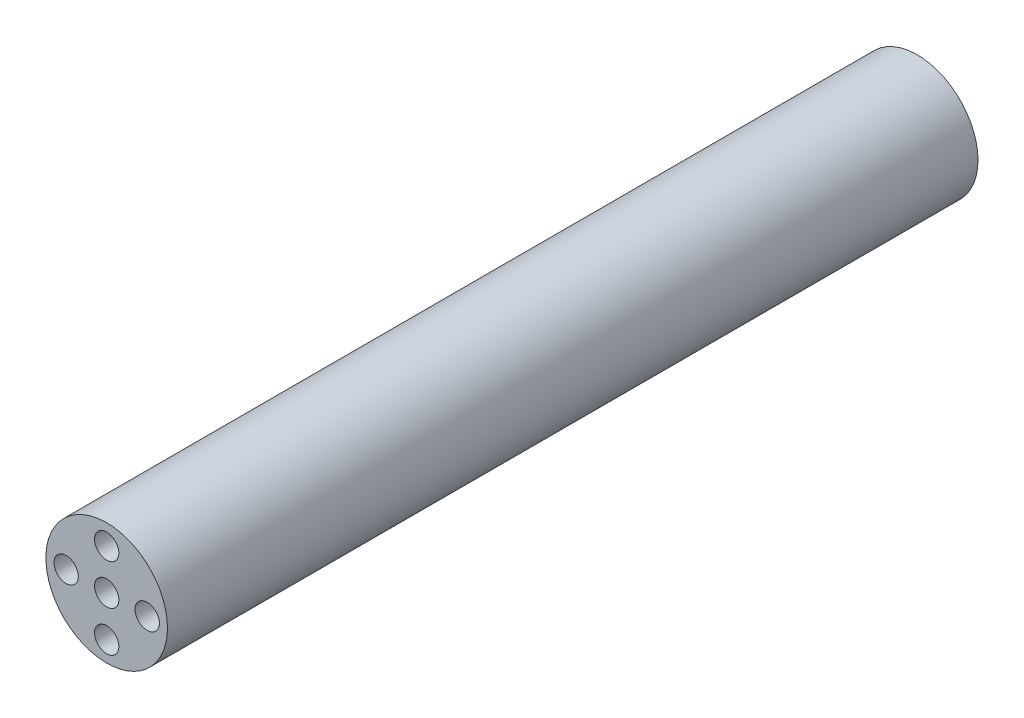
SolidWorks part; units mm, degrees
ref_plane "前视基准面" through (0, 0, 0) normal (0, 0, 1) x (1, 0, 0)
ref_plane "上视基准面" through (0, 0, 0) normal (0, 1, 0) x (1, 0, 0)
ref_plane "右视基准面" through (0, 0, 0) normal (1, 0, 0) x (0, 0, -1)
sketch "草图1" plane through (0, 0, 0) normal (0, 0, 1) x (1, 0, 0)
  circle A0 centre (0, 0) radius 7.5
  circle A1 centre (0, 0) radius 1.5
  circle A2 centre (0, 0) radius 5 construction
  circle A3 centre (0, 5) radius 1.5
  circle A4 centre (5, 0) radius 1.5
  circle A5 centre (0, -5) radius 1.5
  circle A6 centre (-5, 0) radius 1.5
  dimension "D1" = 15
  dimension "D2" = 10
  dimension "D3" = 3
  dimension "D4" = 3
  dimension "D5" = 4
extrude "凸台-拉伸1" add sketch "草图1" along normal blind 100
